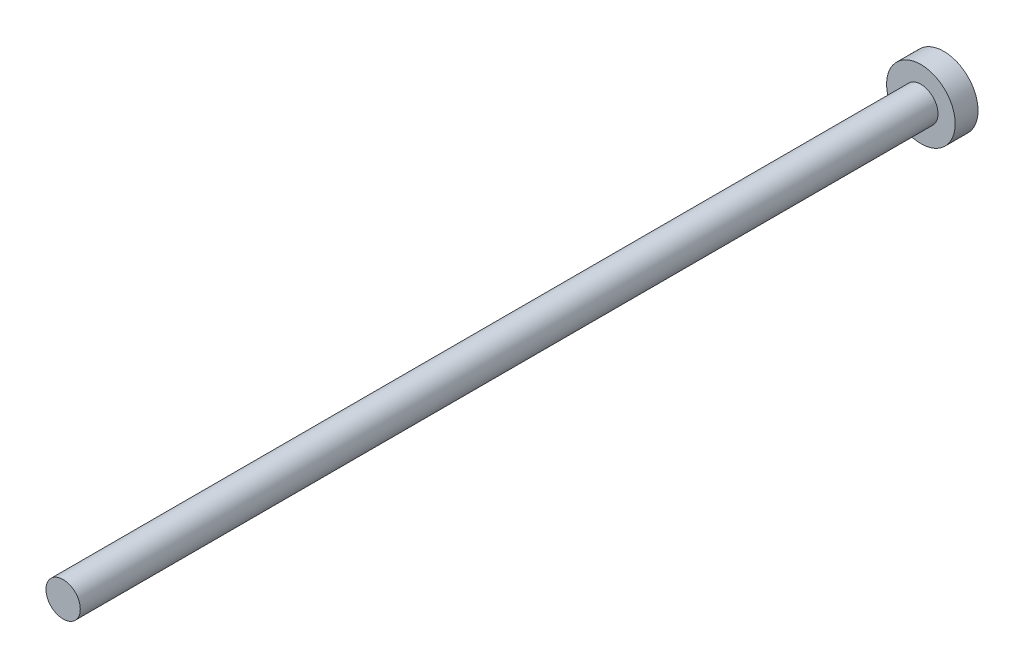
SolidWorks part; units mm, degrees
ref_plane "Front" through (0, 0, 0) normal (0, 0, 1) x (1, 0, 0)
ref_plane "Top" through (0, 0, 0) normal (0, 1, 0) x (1, 0, 0)
ref_plane "Right" through (0, 0, 0) normal (1, 0, 0) x (0, 0, -1)
sketch "Sketch1" plane through (0, 0, 0) normal (0, 0, 1) x (1, 0, 0)
  circle A0 centre (0, 0) radius 1.5
  dimension "D1" = 3
extrude "Boss-Extrude1" add sketch "Sketch1" along normal blind 75
sketch "Sketch2" plane through (0, 0, 0) normal (0, 0, -1) x (-1, 0, 0)
  circle A0 centre (0, 0) radius 3
  dimension "D1" = 6
extrude "Boss-Extrude2" add sketch "Sketch2" along normal blind 2
